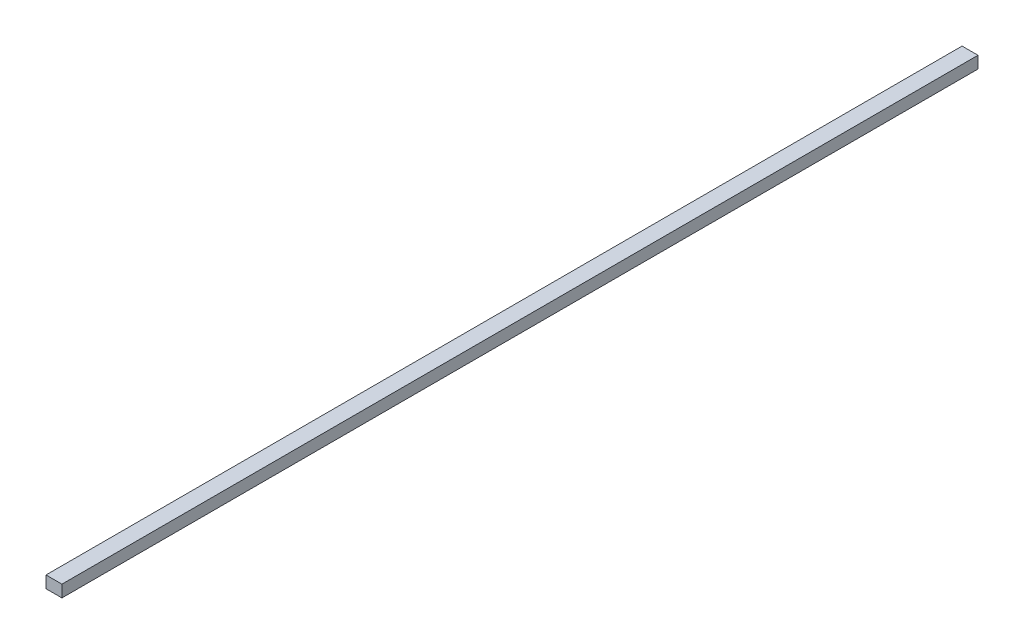
SolidWorks part; units mm, degrees
ref_plane "Front Plane" through (0, 0, 0) normal (0, 0, 1) x (1, 0, 0)
ref_plane "Top Plane" through (0, 0, 0) normal (0, 1, 0) x (1, 0, 0)
ref_plane "Right Plane" through (0, 0, 0) normal (1, 0, 0) x (0, 0, -1)
sketch "Sketch1" plane through (0, 0, 0) normal (0, 1, 0) x (1, 0, 0)
  line L1 (2, -115) -> (-2, -115)
  line L2 (2, -115) -> (2, 115)
  line L3 (2, 115) -> (-2, 115)
  line L4 (-2, -115) -> (-2, 115)
  line L5 (2, -115) -> (-2, 115) construction
  line L6 (2, 115) -> (-2, -115) construction
  point P0 (0, 0)
  dimension "D1" = 4
  dimension "D2" = 230
extrude "Boss-Extrude1" add sketch "Sketch1" along normal blind 3
